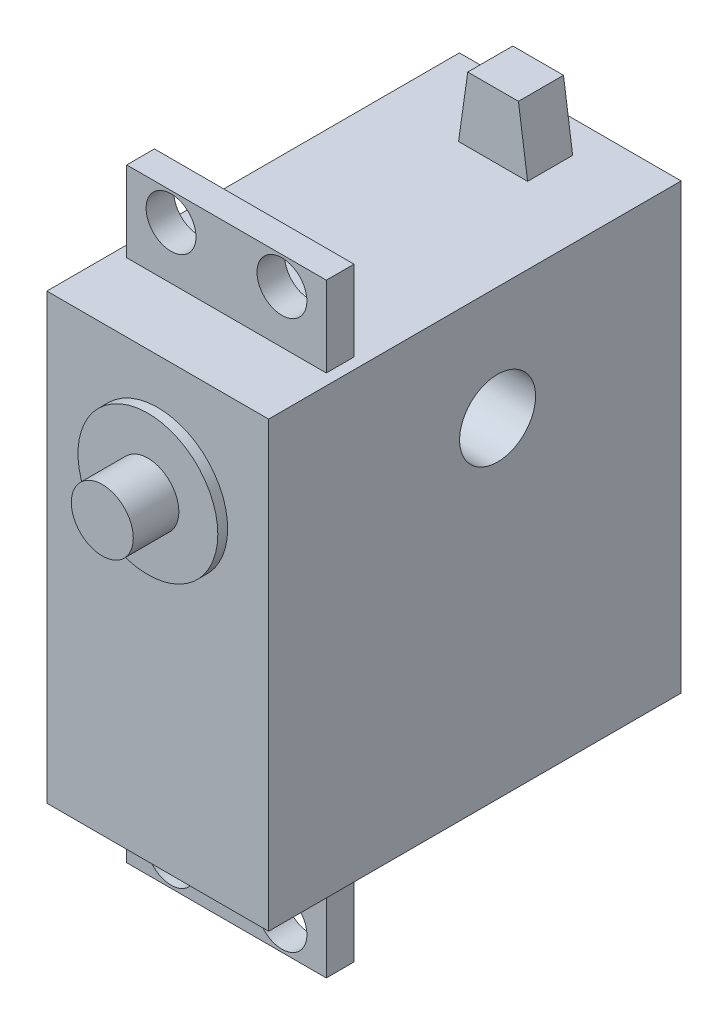
SolidWorks part; units mm, degrees
ref_plane "Front Plane" through (0, 0, 0) normal (0, 0, 1) x (1, 0, 0)
ref_plane "Top Plane" through (0, 0, 0) normal (0, 1, 0) x (1, 0, 0)
ref_plane "Right Plane" through (0, 0, 0) normal (1, 0, 0) x (0, 0, -1)
sketch "Sketch1" plane through (0, 0, 0) normal (0, 0, 1) x (1, 0, 0)
  line L1 (0, 40) -> (20, 40)
  line L2 (0, 40) -> (0, 0)
  line L3 (0, 0) -> (20, 0)
  line L4 (20, 40) -> (20, 0)
  dimension "D1" = 20
  dimension "D2" = 40
extrude "Boss-Extrude1" add sketch "Sketch1" along normal blind 8.7
sketch "Sketch2" plane through (0, 0, 0) normal (0, 0, -1) x (-1, 0, 0)
  line L0 (-20, 40) -> (0, 40) construction
  line L1 (-20, 40) -> (0, 40)
  line L2 (-20, 40) -> (-20, 0)
  line L3 (-20, 0) -> (0, 0)
  line L4 (0, 40) -> (0, 0)
  line L5 (-20, 0) -> (-20, 40) construction
  line L6 (0, 40) -> (0, 0) construction
extrude "Boss-Extrude2" add sketch "Sketch2" along normal blind 28.5
sketch "Sketch3" plane through (0, 0, 0) normal (0, 0, 1) x (1, 0, 0)
  line L0 (0, 0) -> (20, 0) construction
  line L1 (19, 0) -> (1, 0) construction
  line L2 (19, 0) -> (19, -7.25)
  line L3 (20, 40) -> (20, 0)
  line L4 (1, 0) -> (1, -7.25)
  line L5 (20, 40) -> (0, 40) construction
  line L6 (0, 40) -> (0, 0)
  line L7 (19, 47.25) -> (19, 40)
  line L8 (19, 40) -> (1, 40) construction
  line L9 (1, 47.25) -> (1, 40)
  line L10 (20, 0) -> (19, 0)
  line L11 (1, 0) -> (0, 0)
  line L12 (20, 40) -> (19, 40)
  line L13 (1, 40) -> (0, 40)
  line L14 (0, 40) -> (0, 0) construction
  line L15 (20, 0) -> (20, 40) construction
  line L19 (1, 47.25) -> (19, 47.25)
  line L20 (1, -7.25) -> (19, -7.25)
  line L24 (10, 47.25) -> (10, 44.75) construction
  line L25 (10, -7.25) -> (10, -4.75) construction
  line L28 (15, 44.75) -> (15, -4.75) construction
  line L29 (5, 44.75) -> (5, -4.75) construction
  line L30 (5, -4.75) -> (15, -4.75) construction
  line L31 (5, 44.75) -> (15, 44.75) construction
  circle A0 centre (5, -4.75) radius 2.25
  circle A1 centre (15, -4.75) radius 2.25
  circle A2 centre (5, 44.75) radius 2.25
  circle A3 centre (15, 44.75) radius 2.25
  dimension "D6" = 4.5
  dimension "D1" = 18
  dimension "D2" = 54.5
  dimension "D3" = 49.5
  dimension "D4" = 10
extrude "Boss-Extrude3" add sketch "Sketch3" along normal blind 2.5
sketch "Sketch4" plane through (0, 0, 8.7) normal (0, 0, 1) x (1, 0, 0)
  line L76 (0, 29.6) -> (20, 29.6) construction
  line L77 (0, 40) -> (0, 0) construction
  line L78 (20, 0) -> (20, 40) construction
  line L79 (5, 44.75) -> (15, 44.75) construction
  line L80 (20, 40) -> (0, 40) construction
  circle A0 centre (10, 29.6) radius 2.794
  circle A2 centre (5, 44.75) radius 2.25 construction
  circle A3 centre (15, 44.75) radius 2.25 construction
  dimension "D1" = 5.588
  dimension "D2" = 15.15
extrude "Boss-Extrude4" add sketch "Sketch4" along normal blind 5
sketch "Sketch9" plane through (0, 0, -28.5) normal (0, 0, -1) x (-1, 0, 0)
  line L0 (0, 40) -> (-20, 40) construction
  line L1 (-13.1115, 40) -> (-6.8885, 40)
  line L2 (-13.1115, 40) -> (-12.286, 45.842)
  line L3 (-12.286, 45.842) -> (-7.714, 45.842)
  line L4 (-6.8885, 40) -> (-7.714, 45.842)
  line L5 (-10, 40) -> (-10, 45.842) construction
  point P4 (-10, 40)
  dimension "D1" = 6.223
  dimension "D2" = 4.572
  dimension "D3" = 5.842
extrude "Boss-Extrude6" add sketch "Sketch9" against normal blind 6.9596
sketch "Sketch10" plane through (0, 0, 8.7) normal (0, 0, 1) x (1, 0, 0)
  circle A0 centre (10, 29.6) radius 6.3056
  circle A1 centre (10, 29.6) radius 2.794 construction
  dimension "D1" = 12.6111
extrude "Boss-Extrude7" add sketch "Sketch10" along normal blind 0.889
sketch "Sketch11" plane through (0, 0, -28.5) normal (0, 0, -1) x (-1, 0, 0)
  line L0 (-12.286, 45.842) -> (-7.714, 45.842)
  line L1 (-7.714, 45.842) -> (-6.8885, 40)
  line L2 (-6.8885, 40) -> (-13.1115, 40)
  line L3 (-13.1115, 40) -> (-12.286, 45.842)
extrude "Cut-Extrude1" cut sketch "Sketch11" against normal offset from surface (2.8956 mm away) 4.064 up to face at (10, 42.921, -21.5404)
sketch "Sketch15" plane through (20, 0, 0) normal (1, 0, 0) x (0, 0, -1)
  line L0 (11.9458, 40) -> (11.9458, 29.7527) construction
  line L1 (11.9458, 29.7527) -> (28.5, 29.7527) construction
  line L2 (-8.7, 40) -> (28.5, 40) construction
  line L3 (28.5, 40) -> (28.5, 0) construction
  circle A0 centre (11.9458, 29.7527) radius 3.4246
  point P0 (11.9458, 29.7527)
  point P9 (12.8911, 28.6415)
extrude "Cut-Extrude4" cut sketch "Sketch15" against normal up to surface (20 mm away) up to face at (0, 20, -9.9)
